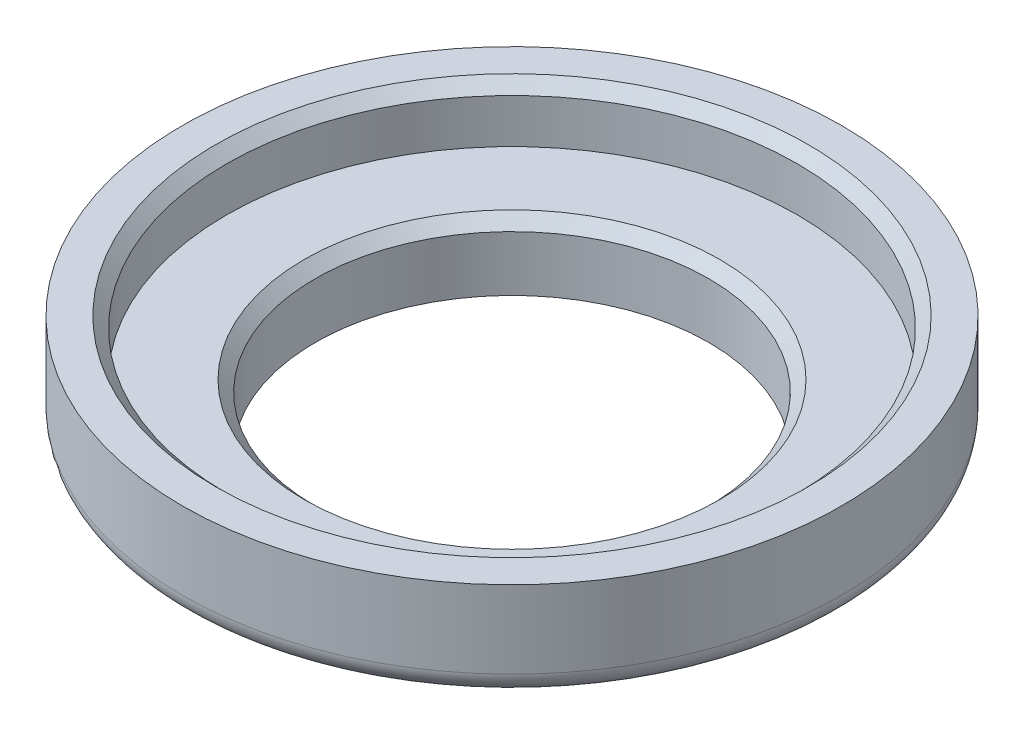
SolidWorks part; units mm, degrees
ref_plane "Plan de face" through (0, 0, 0) normal (0, 0, 1) x (1, 0, 0)
ref_plane "Plan de dessus" through (0, 0, 0) normal (0, 1, 0) x (1, 0, 0)
ref_plane "Plan de droite" through (0, 0, 0) normal (1, 0, 0) x (0, 0, -1)
sketch "Sketch1" plane through (0, 0, 0) normal (0, 0, 1) x (1, 0, 0)
  line L0 (0, 0) -> (0, 23.933) construction
  line L1 (12.9, 5.5) -> (12.9, 3)
  line L2 (12.9, 3) -> (8.9, 3)
  line L3 (8.9, 3) -> (8.9, 0)
  line L4 (8.9, 0) -> (10.9, 0)
  line L5 (10.9, 0) -> (10.9, 1)
  line L6 (10.9, 1) -> (14.9, 1)
  line L7 (14.9, 1) -> (14.9, 5.5)
  line L8 (14.9, 5.5) -> (12.9, 5.5)
  dimension "D1" = 25.8
  dimension "D2" = 17.8
  dimension "D3" = 2
  dimension "D4" = 3
  dimension "D5" = 1
  dimension "D6" = 2.5
revolve "Revolve1" add sketch "Sketch1" angle 360 about L0
fillet "Fillet1" radius 1 1 edges at (0, 1, -14.9)
chamfer "Chamfer1" distance 0.5 angle 45 2 edges at (0, 3, -8.9) (0, 5.5, -12.9)
